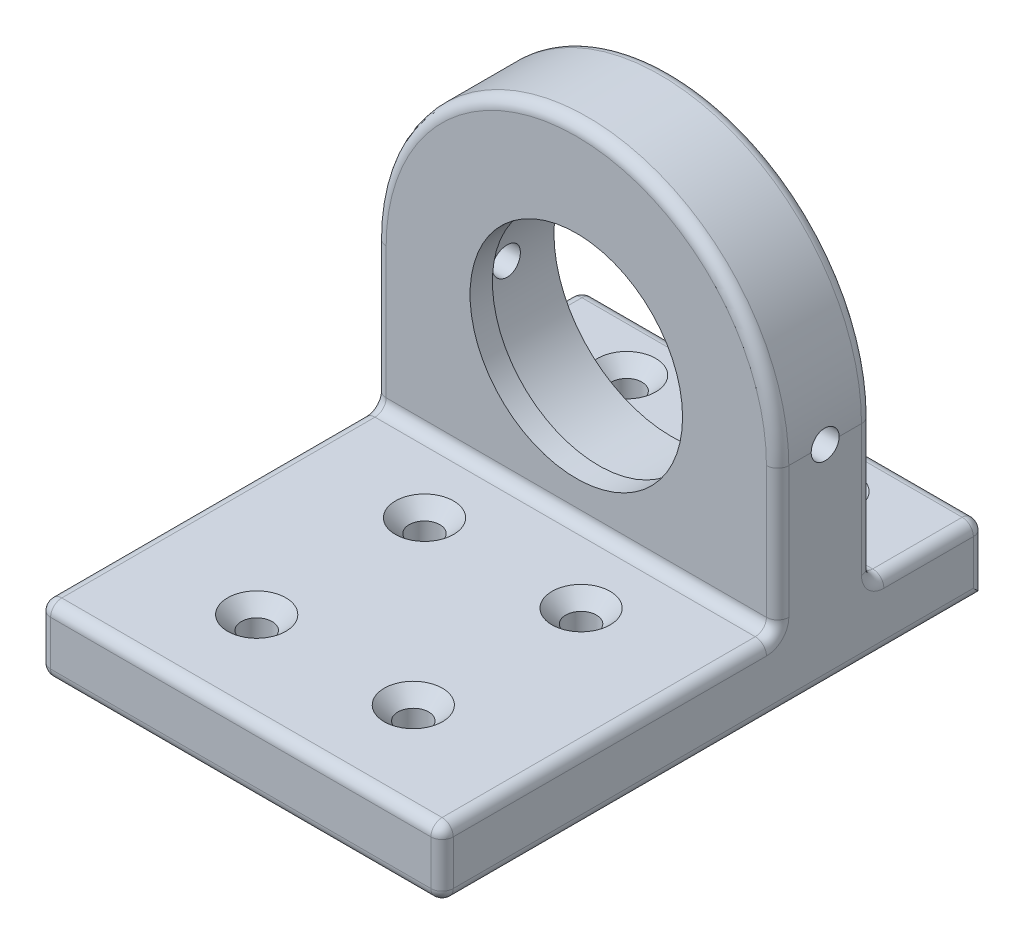
SolidWorks part; units mm, degrees
ref_plane "Front Plane" through (0, 0, 0) normal (0, 0, 1) x (1, 0, 0)
ref_plane "Top Plane" through (0, 0, 0) normal (0, 1, 0) x (1, 0, 0)
ref_plane "Right Plane" through (0, 0, 0) normal (1, 0, 0) x (0, 0, -1)
sketch "Sketch1" plane through (0, 0, 0) normal (0, 0, 1) x (1, 0, 0)
  line L1 (-36, 0) -> (-36, -37.5)
  line L2 (36, 0) -> (36, -37.5)
  line L3 (36, -37.5) -> (-36, -37.5)
  circle A0 centre (0, 0) radius 21
  arc A1 (36, 0) -> (-36, 0) centre (0, 0) ccw
  dimension "D1" = 42
  dimension "D2" = 15
  dimension "D3" = 37.5
extrude "Boss-Extrude1" add sketch "Sketch1" along normal blind 17
sketch "Sketch2" plane through (0, 0, 17) normal (0, 0, 1) x (1, 0, 0)
  line L0 (-36, 0) -> (-36, -37.5) construction
  line L1 (36, -37.5) -> (-36, -37.5)
  line L2 (36, -37.5) -> (36, -25.5)
  line L3 (36, -25.5) -> (-36, -25.5)
  line L4 (-36, -37.5) -> (-36, -25.5)
  dimension "D1" = 12
extrude "Boss-Extrude2" add sketch "Sketch2" along normal blind 60 and the other way blind 37
fillet "Fillet1" radius 2 21 edges at (-36, -12.75, 0) (-36, -12.75, 17) (0, 36, 0) (0, 36, 17) (-36, -37.5, 28.5) (-36, -25.5, 47) (-36, -31.5, 77) (0, -25.5, 77) (0, -37.5, 77) (36, -31.5, 77) (36, -37.5, 28.5) (36, -12.75, 0) (36, -12.75, 17) (36, -25.5, 47) (0, -25.5, 17) (36, -25.5, -10) (36, -31.5, -20) (0, -25.5, -20) (-36, -25.5, -10) (-36, -31.5, -20) (0, -25.5, 0)
sketch "Sketch4" plane through (0, 0, 17) normal (0, 0, 1) x (1, 0, 0)
  circle A0 centre (0, 0) radius 21
  circle A1 centre (0, 0) radius 19
  dimension "D1" = 42
  dimension "D2" = 2
extrude "Boss-Extrude4" add sketch "Sketch4" against normal blind 4
sketch "Sketch5" plane through (0, -25.5, 0) normal (0, 1, 0) x (1, 0, 0)
  line L0 (-34, 10) -> (-18, 10) construction
  line L3 (-34, 18) -> (-34, 2) construction
  line L4 (-18, 10) -> (18, 10) construction
  line L5 (18, 10) -> (34, 10) construction
  line L6 (34, 2) -> (34, 18) construction
  circle A0 centre (-18, 10) radius 3
  circle A1 centre (18, 10) radius 3
  dimension "D1" = 6
  dimension "D2" = 16
sketch "Sketch6" plane through (0, -25.5, 0) normal (0, 1, 0) x (1, 0, 0)
  circle A0 centre (14, -30.1444) radius 2.5
  circle A1 centre (14, -60.1444) radius 2.5
  circle A2 centre (-14, -60.1444) radius 2.5
  circle A3 centre (-14, -30.1444) radius 2.5
  dimension "D1" = 5
sketch "Sketch7" plane through (36, 0, 0) normal (1, 0, 0) x (0, 0, -1)
  line L0 (-15, 0) -> (-2, 0) construction
  circle A0 centre (-8.5, 0) radius 2.5
  dimension "D1" = 5
extrude "Cut-Extrude3" cut sketch "Sketch7" against normal through all
sketch "Sketch8" plane through (0, 0, 17) normal (0, 0, 1) x (1, 0, 0)
hole_wizard "CSK for M5 Countersunk Raised Head Screw1" positions "3DSketch1" profile "Sketch9" countersink size "M5" standard "DIN" end condition through all
sketch3d "3DSketch1"
  point P0 (-14, -25.5, 60.1444)
  point P9 (14, -25.5, 60.1444)
  point P12 (-18, -25.5, -10)
  point P15 (18, -25.5, -10)
  point P21 (-14, -25.5, 30.1444)
  point P24 (14, -25.5, 30.1444)
sketch "Sketch9" plane through (-14, -25.5, 60.1444) normal (1, 0, 0) x (0, 0, 1)
  line L0 (0, 0) -> (0, 12)
  line L1 (0, 12) -> (2.75, 12)
  line L2 (2.75, 12) -> (2.75, 2.45)
  line L3 (2.75, 2.45) -> (5.2, 0)
  line L5 (5.2, 0) -> (0, 0)
  line L6 (-2.75, 2.45) -> (-5.2, 0) construction
  line L11 (0, -6.35) -> (0, 107.95) construction
  dimension "Thru Hole Dia." = 5.5
  dimension "Thru Hole Depth" = 12
  dimension "Near C'Sink Dia." = 10.4
  dimension "Near C'Sink Angle" = 90
